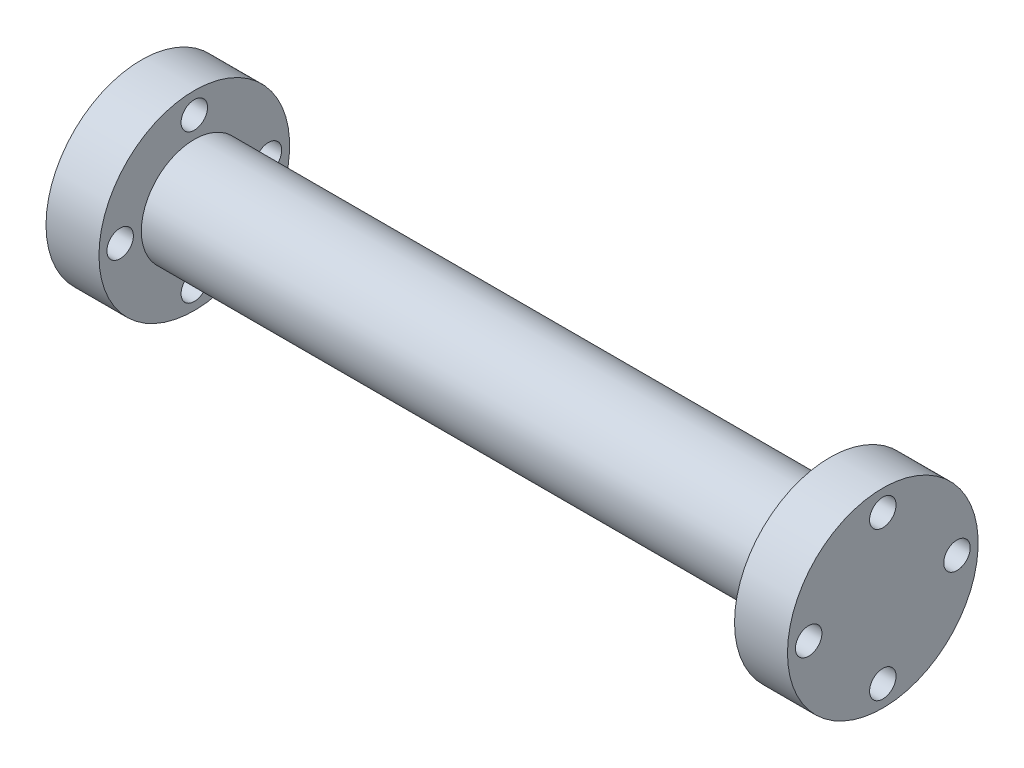
SolidWorks part; units mm, degrees
ref_plane "前视基准面" through (0, 0, 0) normal (0, 0, 1) x (1, 0, 0)
ref_plane "上视基准面" through (0, 0, 0) normal (0, 1, 0) x (1, 0, 0)
ref_plane "右视基准面" through (0, 0, 0) normal (1, 0, 0) x (0, 0, -1)
sketch "草图1" plane through (0, 0, 0) normal (0, 0, 1) x (1, 0, 0)
  line L0 (-43.9051, 0) -> (26.0949, 0)
  line L1 (26.0949, 0) -> (26.0949, 9)
  line L2 (26.0949, 9) -> (21.0949, 9)
  line L3 (21.0949, 9) -> (21.0949, 5)
  line L4 (21.0949, 5) -> (-38.9051, 5)
  line L5 (-38.9051, 5) -> (-38.9051, 9)
  line L6 (-38.9051, 9) -> (-43.9051, 9)
  line L7 (-43.9051, 9) -> (-43.9051, 0)
revolve "旋转1" add sketch "草图1" angle 360 about L0
sketch "草图2" plane through (-43.9051, 0, 0) normal (-1, 0, 0) x (0, 0, 1)
  circle A0 centre (0, 0) radius 7
  point P3 (7, 0)
  point P4 (0, 7)
  point P5 (-7, 0)
  point P6 (0, -7)
hole_wizard "M3 螺纹孔1" positions "草图7" profile "草图8" tap size "M3" standard "ISO"
sketch "草图7" plane through (-43.9051, 0, 0) normal (-1, 0, 0) x (0, 0, 1)
  point P0 (7, 0)
  point P3 (0, 7)
  point P6 (-7, 0)
  point P9 (0, -7)
sketch "草图8" plane through (-43.9051, 0, 7) normal (0, 1, 0) x (0, 0, 1)
  line L0 (0, 0) -> (0, 5.7511)
  line L1 (0, 5.7511) -> (1.25, 5)
  line L2 (1.25, 5) -> (1.25, 0)
  line L5 (1.25, 0) -> (0, 0)
  line L10 (0, 5.7511) -> (-1.25, 5) construction
  line L11 (0, -6.35) -> (0, 107.95) construction
  dimension "螺纹孔钻头直径" = 2.5
  dimension "螺纹孔钻头深度" = 5
  dimension "导头角度" = 118
cosmetic thread "孔螺蚊线1"
cosmetic thread "孔螺蚊线2"
cosmetic thread "孔螺蚊线3"
cosmetic thread "孔螺蚊线4"
hole_wizard "M3 螺纹孔2" positions "草图9" profile "草图10" tap size "M3" standard "ISO"
sketch "草图9" plane through (26.0949, 0, 0) normal (1, 0, 0) x (0, 0, -1)
  point P0 (0, -7)
  point P3 (7, 0)
  point P6 (0, 7)
  point P9 (-7, 0)
sketch "草图10" plane through (26.0949, -7, 0) normal (0, 1, 0) x (0, 0, -1)
  line L0 (0, 0) -> (0, 5.7511)
  line L1 (0, 5.7511) -> (1.25, 5)
  line L2 (1.25, 5) -> (1.25, 0)
  line L5 (1.25, 0) -> (0, 0)
  line L10 (0, 5.7511) -> (-1.25, 5) construction
  line L11 (0, -6.35) -> (0, 107.95) construction
  dimension "螺纹孔钻头直径" = 2.5
  dimension "螺纹孔钻头深度" = 5
  dimension "导头角度" = 118
cosmetic thread "孔螺蚊线5"
cosmetic thread "孔螺蚊线6"
cosmetic thread "孔螺蚊线7"
cosmetic thread "孔螺蚊线8"
